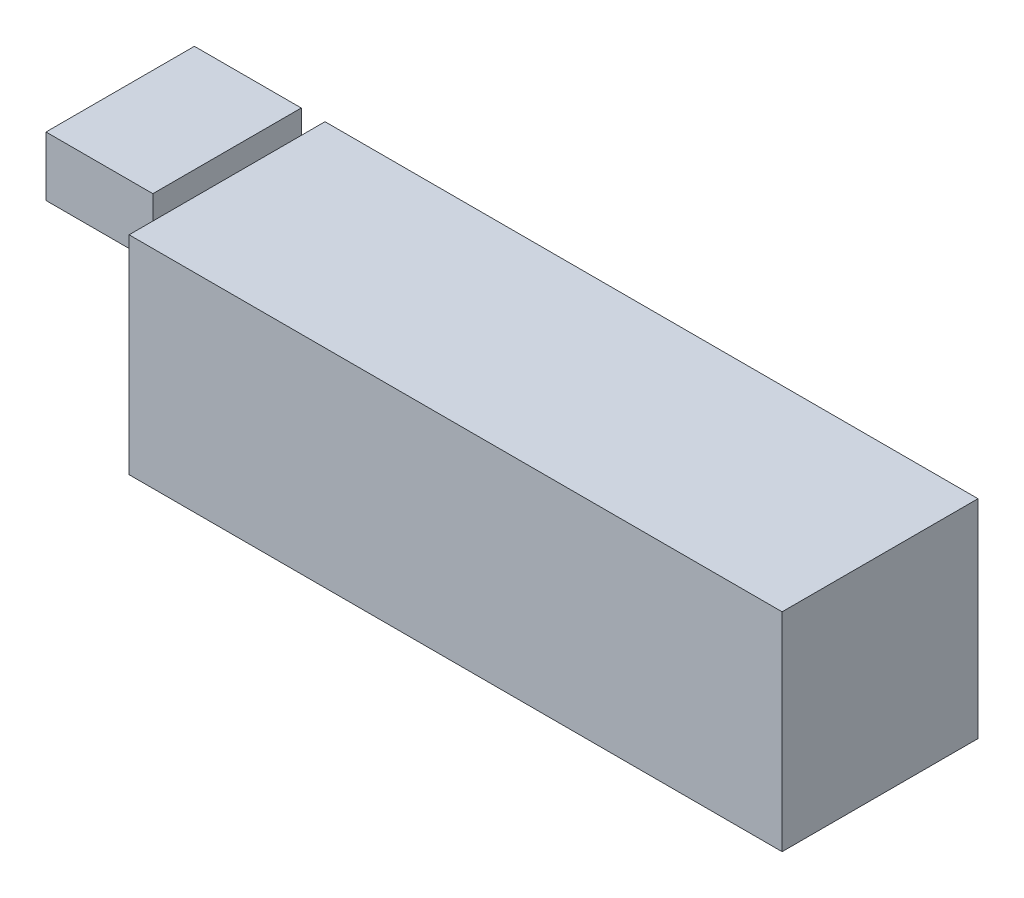
SolidWorks part; units mm, degrees
material "Настроенная пользователем пластмасса"
ref_plane "Спереди" through (0, 0, 0) normal (0, 0, 1) x (1, 0, 0)
ref_plane "Сверху" through (0, 0, 0) normal (0, 1, 0) x (1, 0, 0)
ref_plane "Справа" through (0, 0, 0) normal (1, 0, 0) x (0, 0, -1)
sketch "Эскиз1" plane through (0, 0, 0) normal (0, 0, 1) x (1, 0, 0)
  line L1 (0, 0) -> (110, 0)
  line L2 (0, 0) -> (0, 35)
  line L3 (0, 35) -> (110, 35)
  line L4 (110, 0) -> (110, 35)
  dimension "D1" = 110
  dimension "D2" = 35
extrude "Бобышка-Вытянуть1" add sketch "Эскиз1" along normal blind 33
sketch "Эскиз2" plane through (0, 0, 0) normal (-1, 0, 0) x (0, 0, 1)
  line L0 (16.5, 35) -> (16.5, 16.7306) construction
  line L1 (33, 35) -> (0, 35) construction
  line L3 (4, 39) -> (29, 39)
  line L4 (4, 39) -> (4, 29)
  line L5 (4, 29) -> (29, 29)
  line L6 (29, 39) -> (29, 29)
  line L7 (4, 39) -> (29, 29) construction
  line L8 (4, 29) -> (29, 39) construction
  point P4 (16.5, 34)
  dimension "D1" = 25
  dimension "D2" = 10
  dimension "D3" = 4
extrude "Бобышка-Вытянуть2" add sketch "Эскиз2" along normal blind 18
